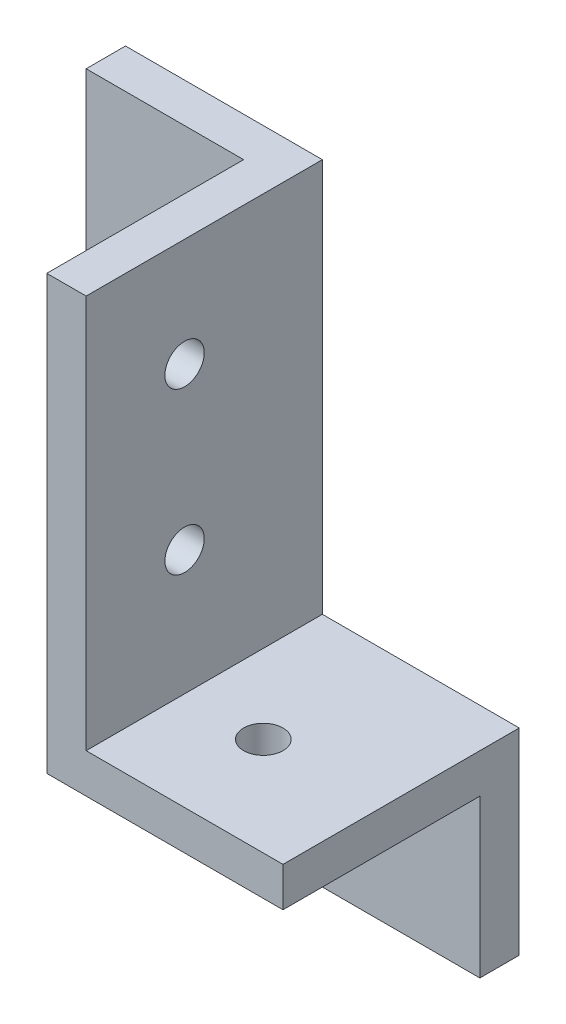
SolidWorks part; units mm, degrees
ref_plane "Front Plane" through (0, 0, 0) normal (0, 0, 1) x (1, 0, 0)
ref_plane "Top Plane" through (0, 0, 0) normal (0, 1, 0) x (1, 0, 0)
ref_plane "Right Plane" through (0, 0, 0) normal (1, 0, 0) x (0, 0, -1)
sketch "Sketch1" plane through (0, 0, 0) normal (0, 0, 1) x (1, 0, 0)
  line L0 (0, 150) -> (50, 150)
  line L1 (0, 0) -> (100, 0)
  line L2 (0, 0) -> (0, 150)
  line L3 (100, 50) -> (100, 0)
  line L5 (50, 150) -> (50, 50)
  line L6 (50, 50) -> (100, 50)
  dimension "D1" = 150
extrude "Boss-Extrude1" add sketch "Sketch1" along normal blind 10
sketch "Sketch2" plane through (0, 0, 10) normal (0, 0, 1) x (1, 0, 0)
  line L0 (40, 150) -> (40, 40)
  line L1 (50, 150) -> (0, 150) construction
  line L2 (40, 40) -> (100, 40)
  line L3 (100, 0) -> (100, 50) construction
  line L4 (100, 40) -> (100, 50)
  line L5 (100, 50) -> (50, 50)
  line L6 (50, 50) -> (50, 150)
  line L7 (50, 150) -> (40, 150)
  dimension "D1" = 10
  dimension "D2" = 10
extrude "Boss-Extrude2" add sketch "Sketch2" along normal blind 50
sketch "Sketch3" plane through (0, 0, 10) normal (0, 0, 1) x (1, 0, 0)
  line L0 (20, 150) -> (20, 0) construction
  line L1 (40, 150) -> (0, 150) construction
  line L2 (0, 0) -> (100, 0) construction
  line L3 (100, 20) -> (0, 20) construction
  line L4 (100, 0) -> (100, 40) construction
  line L5 (0, 150) -> (0, 0) construction
  circle A0 centre (20, 20) radius 5
  circle A1 centre (20, 120) radius 5
  circle A2 centre (20, 75) radius 5
  circle A3 centre (70, 20) radius 5
  dimension "D2" = 10
  dimension "D3" = 10
  dimension "D5" = 10
  dimension "D6" = 10
  dimension "D1" = 30
  dimension "D4" = 30
extrude "Cut-Extrude1" cut sketch "Sketch3" against normal through all
sketch "Sketch4" plane through (40, 0, 0) normal (-1, 0, 0) x (0, 0, 1)
  line L0 (35, 150) -> (35, 40) construction
  line L1 (60, 150) -> (10, 150) construction
  line L2 (60, 40) -> (10, 40) construction
  circle A0 centre (35, 122.5556) radius 5
  circle A1 centre (35, 81.6855) radius 5
  dimension "D1" = 10
  dimension "D2" = 10
extrude "Cut-Extrude2" cut sketch "Sketch4" against normal blind 10
sketch "Sketch5" plane through (0, 40, 0) normal (0, -1, 0) x (1, 0, 0)
  line L0 (40, 35) -> (100, 35) construction
  line L1 (40, 60) -> (40, 10) construction
  line L2 (100, 60) -> (100, 10) construction
  circle A0 centre (70, 35) radius 5
  dimension "D1" = 10
extrude "Cut-Extrude3" cut sketch "Sketch5" against normal blind 10
